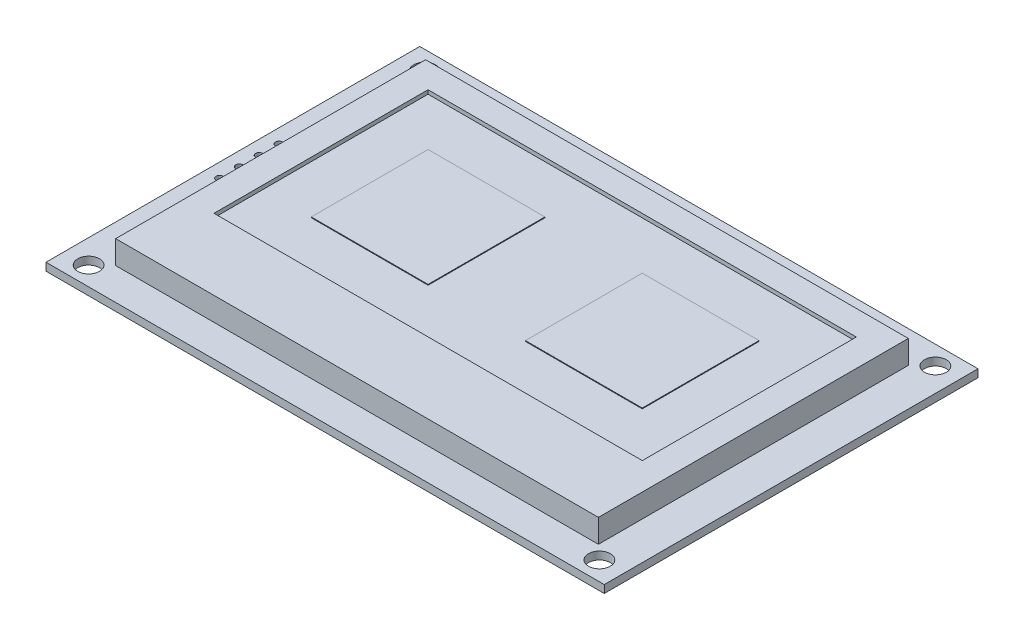
SolidWorks part; units mm, degrees
ref_plane "Front Plane" through (0, 0, 0) normal (0, 0, 1) x (1, 0, 0)
ref_plane "Top Plane" through (0, 0, 0) normal (0, 1, 0) x (1, 0, 0)
ref_plane "Right Plane" through (0, 0, 0) normal (1, 0, 0) x (0, 0, -1)
sketch "Sketch1" plane through (0, 0, 0) normal (0, 1, 0) x (1, 0, 0)
  line L1 (-35.85, -24) -> (35.85, -24)
  line L2 (-35.85, -24) -> (-35.85, 24)
  line L3 (-35.85, 24) -> (35.85, 24)
  line L4 (35.85, -24) -> (35.85, 24)
  line L5 (-35.85, -24) -> (35.85, 24) construction
  line L6 (-35.85, 24) -> (35.85, -24) construction
  point P0 (0, 0)
  dimension "D1" = 48
  dimension "D2" = 71.7
extrude "Boss-Extrude1" add sketch "Sketch1" along normal blind 1
sketch "Sketch2" plane through (0, 1, 0) normal (0, 1, 0) x (1, 0, 0)
  line L1 (32.8, -21.575) -> (-32.8, -21.575) construction
  line L2 (32.8, -21.575) -> (32.8, 21.575) construction
  line L3 (32.8, 21.575) -> (-32.8, 21.575) construction
  line L4 (-32.8, -21.575) -> (-32.8, 21.575) construction
  line L5 (32.8, -21.575) -> (-32.8, 21.575) construction
  line L6 (32.8, 21.575) -> (-32.8, -21.575) construction
  circle A0 centre (-32.8, 21.575) radius 1.4
  circle A1 centre (32.8, 21.575) radius 1.4
  circle A2 centre (-32.8, -21.575) radius 1.4
  circle A3 centre (32.8, -21.575) radius 1.4
  point P0 (0, 0)
  dimension "D3" = 2.8
  dimension "D1" = 43.15
  dimension "D2" = 65.6
extrude "Cut-Extrude1" cut sketch "Sketch2" against normal through all
sketch "Sketch3" plane through (0, 1, 0) normal (0, 1, 0) x (1, 0, 0)
  line L1 (-31, -19.9) -> (31, -19.9)
  line L2 (-31, -19.9) -> (-31, 19.9)
  line L3 (-31, 19.9) -> (31, 19.9)
  line L4 (31, -19.9) -> (31, 19.9)
  line L5 (-31, -19.9) -> (31, 19.9) construction
  line L6 (-31, 19.9) -> (31, -19.9) construction
  point P0 (0, 0)
  dimension "D1" = 62
  dimension "D2" = 39.8
extrude "Boss-Extrude2" add sketch "Sketch3" along normal blind 4 from surface at -1 starting at face at (32.8, 0, -20.175)
sketch "Sketch4" plane through (0, 4, 0) normal (0, 1, 0) x (1, 0, 0)
  line L0 (0, 2.976) -> (0, 0) construction
  line L1 (-27.505, 16.721) -> (27.505, 16.721)
  line L2 (-27.505, 16.721) -> (-27.505, -10.769)
  line L3 (-27.505, -10.769) -> (27.505, -10.769)
  line L4 (27.505, 16.721) -> (27.505, -10.769)
  line L5 (-27.505, 16.721) -> (27.505, -10.769) construction
  line L6 (-27.505, -10.769) -> (27.505, 16.721) construction
  line L8 (35.85, 24) -> (-35.85, 24) construction
  point P0 (0, 2.976)
  dimension "D1" = 55.01
  dimension "D2" = 27.49
  dimension "D3" = 21.024
extrude "Cut-Extrude2" cut sketch "Sketch4" against normal blind 0.5
sketch "Sketch5" plane through (0, 1, 0) normal (0, 1, 0) x (1, 0, 0)
  line L0 (-35.85, 21.55) -> (0, 21.55) construction
  line L1 (-35.85, 24) -> (-35.85, -24) construction
  line L2 (0, 21.55) -> (0, 0) construction
  line L3 (35.85, 24) -> (-35.85, 24) construction
  circle A1 centre (-4.66, 21.55) radius 0.45
  dimension "D2" = 0.9
  dimension "D1" = 2.45
  dimension "D3" = 31.19
extrude "Cut-Extrude3" cut sketch "Sketch5" against normal through all
pattern_linear "LPattern1" count 4 spacing 2.54 along (1, 0, 0) of "Cut-Extrude3"
sketch "Sketch6" plane through (0, 1, 0) normal (0, 1, 0) x (1, 0, 0)
  line L0 (-34.05, 24) -> (-34.05, 4.11) construction
  line L1 (35.85, 24) -> (-35.85, 24) construction
  line L2 (-35.85, 24) -> (-35.85, -24) construction
  circle A0 centre (-34.05, 4.11) radius 0.45
  dimension "D1" = 0.9
  dimension "D2" = 19.89
  dimension "D3" = 1.8
extrude "Cut-Extrude4" cut sketch "Sketch6" against normal through all
pattern_linear "LPattern2" count 4 spacing 2.54 along (0, 0, 1) of "Cut-Extrude4"
sketch "Sketch7" plane through (0, 3.5, 0) normal (0, 1, 0) x (1, 0, 0)
  line L0 (0, 16.721) -> (0, -10.769) construction
  line L1 (-27.505, -10.769) -> (27.505, -10.769) construction
  line L2 (0, 2.976) -> (-13.7525, 2.976) construction
  line L3 (27.505, 16.721) -> (-27.505, 16.721) construction
  line L4 (-6.2525, -4.524) -> (-21.2525, -4.524)
  line L5 (-6.2525, -4.524) -> (-6.2525, 10.476)
  line L6 (-6.2525, 10.476) -> (-21.2525, 10.476)
  line L7 (-21.2525, -4.524) -> (-21.2525, 10.476)
  line L8 (-6.2525, -4.524) -> (-21.2525, 10.476) construction
  line L9 (-6.2525, 10.476) -> (-21.2525, -4.524) construction
  line L10 (0, 16.721) -> (-27.505, 16.721) construction
  line L11 (-13.7525, 2.976) -> (-13.7525, 16.721) construction
  point P10 (-13.7525, 16.721)
  dimension "D1" = 15
  dimension "D2" = 15
extrude "Boss-Extrude3" add sketch "Sketch7" along normal blind 0.1
mirror "Mirror1" about plane through (0, 0, 0) normal (1, 0, 0) of "Boss-Extrude3"
